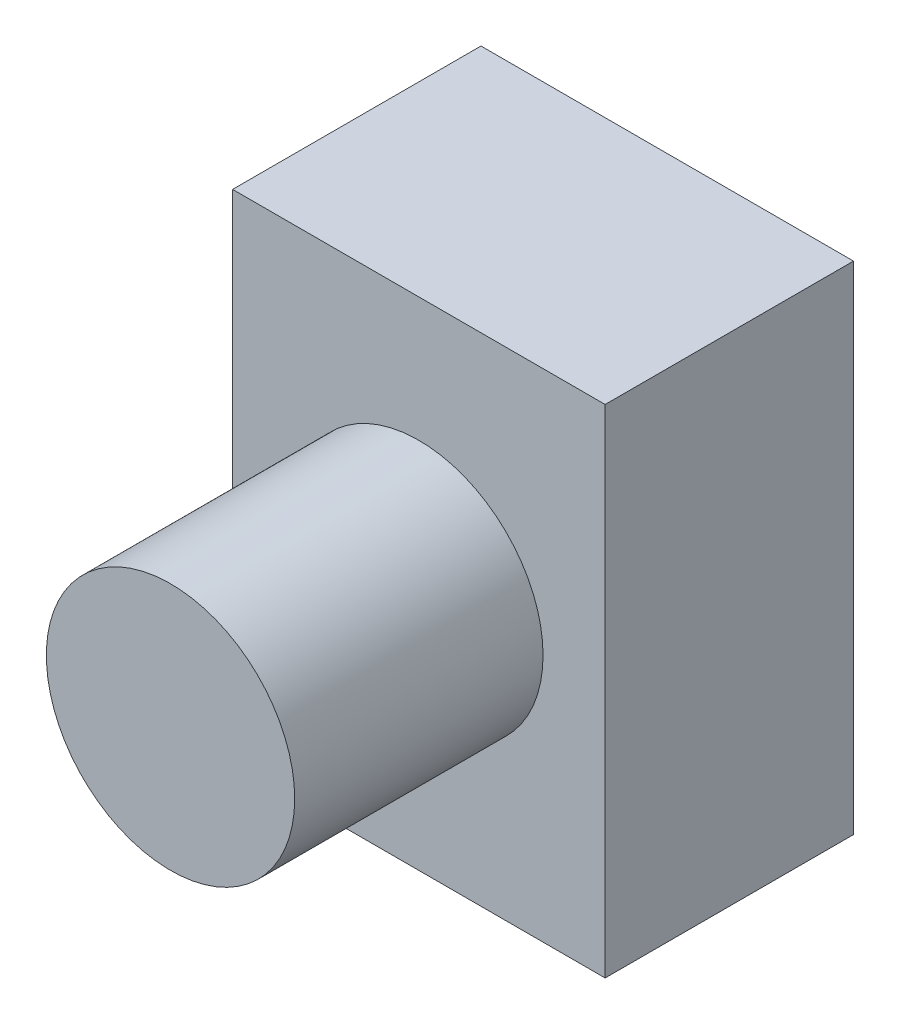
SolidWorks part; units mm, degrees
ref_plane "Front Plane" through (0, 0, 0) normal (0, 0, 1) x (1, 0, 0)
ref_plane "Top Plane" through (0, 0, 0) normal (0, 1, 0) x (1, 0, 0)
ref_plane "Right Plane" through (0, 0, 0) normal (1, 0, 0) x (0, 0, -1)
sketch "Sketch1" plane through (0, 0, 0) normal (0, 0, 1) x (1, 0, 0)
  line L1 (-15, 20) -> (15, 20)
  line L2 (-15, 20) -> (-15, -20)
  line L3 (-15, -20) -> (15, -20)
  line L4 (15, 20) -> (15, -20)
  line L5 (-15, 20) -> (15, -20) construction
  line L6 (-15, -20) -> (15, 20) construction
  point P0 (0, 0)
  dimension "D1" = 30
  dimension "D2" = 40
extrude "Boss-Extrude1" add sketch "Sketch1" along normal blind 20
sketch "Sketch2" plane through (0, 0, 20) normal (0, 0, 1) x (1, 0, 0)
  circle A0 centre (0, 0) radius 10
extrude "Boss-Extrude2" add sketch "Sketch2" along normal blind 20
